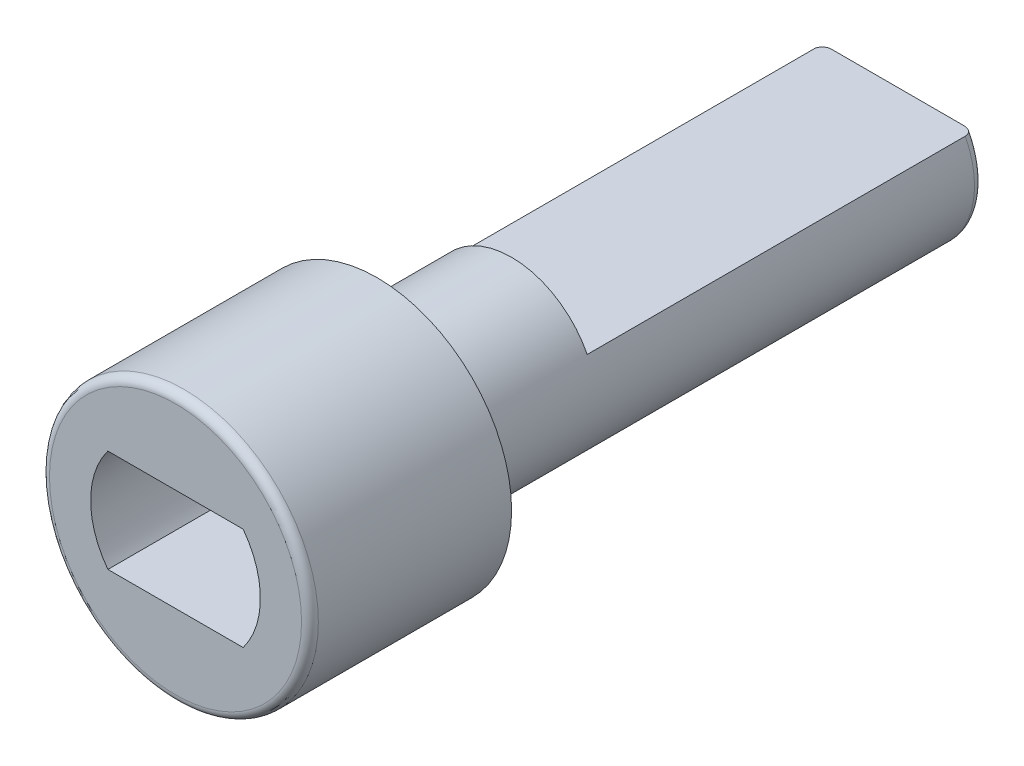
SolidWorks part; units mm, degrees
material "Custom Plastic"
ref_plane "Front Plane" through (0, 0, 0) normal (0, 0, 1) x (1, 0, 0)
ref_plane "Top Plane" through (0, 0, 0) normal (0, 1, 0) x (1, 0, 0)
ref_plane "Right Plane" through (0, 0, 0) normal (1, 0, 0) x (0, 0, -1)
sketch "Sketch1" plane through (0, 0, 0) normal (0, 0, 1) x (1, 0, 0)
  circle A0 centre (0, 0) radius 2.525
  dimension "D1" = 5.05
extrude "Boss-Extrude1" add sketch "Sketch1" along normal blind 15.5
sketch "Sketch2" plane through (0, 0, 15.5) normal (0, 0, 1) x (1, 0, 0)
  circle A0 centre (0, 0) radius 4
  circle A1 centre (0, 0) radius 2.525 construction
  dimension "D1" = 8
extrude "Boss-Extrude2" add sketch "Sketch2" along normal blind 6 contours A0
sketch "Sketch3" plane through (0, 0, 21.5) normal (0, 0, 1) x (1, 0, 0)
  line L1 (-2.0125, 1.525) -> (2.0125, 1.525)
  line L3 (-2.0125, -1.525) -> (2.0125, -1.525)
  line L5 (-2.0125, 1.525) -> (2.0125, -1.525) construction
  line L6 (-2.0125, -1.525) -> (2.0125, 1.525) construction
  arc A0 (-2.0125, 1.525) -> (-2.0125, -1.525) centre (0, 0) ccw
  arc A1 (2.0125, -1.525) -> (2.0125, 1.525) centre (0, 0) ccw
  dimension "D1" = 5.05
  dimension "D2" = 3.05
extrude "Cut-Extrude1" cut sketch "Sketch3" against normal blind 5 contours L1 A1 L3 A0
fillet "Fillet2" radius 0.25 1 edges at (4, 0, 21.5)
fillet "Fillet3" radius 0.25 1 edges at (2.525, 0, 0)
sketch "Sketch4" plane through (0, 0, 0) normal (0, 0, -1) x (-1, 0, 0)
  line L1 (-2.25, 1.1459) -> (2.25, 1.1459)
  arc A1 (-2.25, 1.1459) -> (2.25, 1.1459) centre (0, 0) cw
  circle A2 centre (0, 0) radius 2.525 construction
  point P0 (0, 0)
  dimension "D1" = 4.5
extrude "Cut-Extrude2" cut sketch "Sketch4" against normal blind 11.5 contours L1 A1
